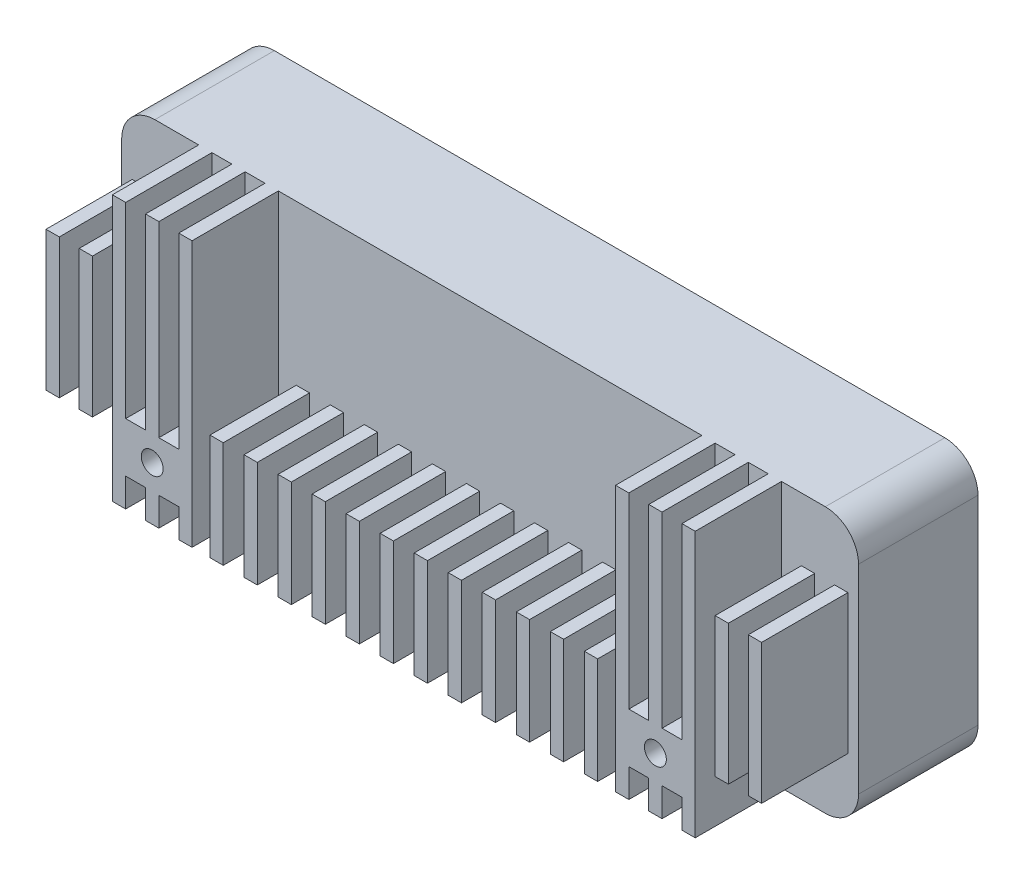
SolidWorks part; units mm, degrees
ref_plane "Plano frontal" through (0, 0, 0) normal (0, 0, 1) x (1, 0, 0)
ref_plane "Plano superior" through (0, 0, 0) normal (0, 1, 0) x (1, 0, 0)
ref_plane "Plano direito" through (0, 0, 0) normal (1, 0, 0) x (0, 0, -1)
sketch "Esboço1" plane through (0, 0, 0) normal (0, 0, 1) x (1, 0, 0)
  line L1 (55.5, -20) -> (-55.5, -20)
  line L2 (55.5, -20) -> (55.5, 20)
  line L3 (55.5, 20) -> (-55.5, 20)
  line L4 (-55.5, -20) -> (-55.5, 20)
  line L5 (55.5, -20) -> (-55.5, 20) construction
  line L6 (55.5, 20) -> (-55.5, -20) construction
  point P0 (0, 0)
  dimension "D1" = 40
  dimension "D2" = 111
extrude "Ressalto-extrusão1" add sketch "Esboço1" along normal blind 18
sketch "Esboço2" plane through (0, 0, 18) normal (0, 0, 1) x (1, 0, 0)
  line L0 (-55.5, -20) -> (55.5, -20) construction
  line L1 (-29.2, -4) -> (-27.2, -4)
  line L2 (-29.2, -4) -> (-29.2, -20)
  line L3 (-29.2, -20) -> (-27.2, -20)
  line L4 (-27.2, -4) -> (-27.2, -20)
  line L5 (-55.5, 20) -> (-55.5, -20) construction
  line L6 (-24.0727, -4) -> (-24.0727, -20)
  line L7 (-24.0727, -4) -> (-22.0727, -4)
  line L8 (-22.0727, -4) -> (-22.0727, -20)
  line L9 (-24.0727, -20) -> (-22.0727, -20)
  line L10 (-18.9455, -4) -> (-18.9455, -20)
  line L11 (-18.9455, -4) -> (-16.9455, -4)
  line L12 (-16.9455, -4) -> (-16.9455, -20)
  line L13 (-18.9455, -20) -> (-16.9455, -20)
  line L14 (-13.8182, -4) -> (-13.8182, -20)
  line L15 (-13.8182, -4) -> (-11.8182, -4)
  line L16 (-11.8182, -4) -> (-11.8182, -20)
  line L17 (-13.8182, -20) -> (-11.8182, -20)
  line L18 (-8.6909, -4) -> (-8.6909, -20)
  line L19 (-8.6909, -4) -> (-6.6909, -4)
  line L20 (-6.6909, -4) -> (-6.6909, -20)
  line L21 (-8.6909, -20) -> (-6.6909, -20)
  line L22 (-3.5636, -4) -> (-3.5636, -20)
  line L23 (-3.5636, -4) -> (-1.5636, -4)
  line L24 (-1.5636, -4) -> (-1.5636, -20)
  line L25 (-3.5636, -20) -> (-1.5636, -20)
  line L26 (1.5636, -4) -> (1.5636, -20)
  line L27 (1.5636, -4) -> (3.5636, -4)
  line L28 (3.5636, -4) -> (3.5636, -20)
  line L29 (1.5636, -20) -> (3.5636, -20)
  line L30 (6.6909, -4) -> (6.6909, -20)
  line L31 (6.6909, -4) -> (8.6909, -4)
  line L32 (8.6909, -4) -> (8.6909, -20)
  line L33 (6.6909, -20) -> (8.6909, -20)
  line L34 (11.8182, -4) -> (11.8182, -20)
  line L35 (11.8182, -4) -> (13.8182, -4)
  line L36 (13.8182, -4) -> (13.8182, -20)
  line L37 (11.8182, -20) -> (13.8182, -20)
  line L38 (16.9455, -4) -> (16.9455, -20)
  line L39 (16.9455, -4) -> (18.9455, -4)
  line L40 (18.9455, -4) -> (18.9455, -20)
  line L41 (16.9455, -20) -> (18.9455, -20)
  line L42 (22.0727, -4) -> (22.0727, -20)
  line L43 (22.0727, -4) -> (24.0727, -4)
  line L44 (24.0727, -4) -> (24.0727, -20)
  line L45 (22.0727, -20) -> (24.0727, -20)
  line L46 (27.2, -4) -> (27.2, -20)
  line L47 (27.2, -4) -> (29.2, -4)
  line L48 (29.2, -4) -> (29.2, -20)
  line L49 (27.2, -20) -> (29.2, -20)
  line L50 (55.5, -20) -> (55.5, 20) construction
  line L51 (-48.9, 10.5) -> (-48.9, -10.5)
  line L52 (-53.9, 10.5) -> (-51.9, 10.5)
  line L53 (-53.9, 10.5) -> (-53.9, -10.5)
  line L54 (-53.9, -10.5) -> (-51.9, -10.5)
  line L55 (-51.9, 10.5) -> (-51.9, -10.5)
  line L56 (-48.9, 10.5) -> (-46.9, 10.5)
  line L57 (-46.9, 10.5) -> (-46.9, -10.5)
  line L58 (-48.9, -10.5) -> (-46.9, -10.5)
  line L59 (-53.9, 10.5) -> (-48.9, 10.5) construction
  line L60 (55.5, 20) -> (-55.5, 20) construction
  line L61 (-43.9, 20) -> (-41.9, 20)
  line L62 (-43.9, 20) -> (-43.9, -20)
  line L63 (-43.9, -20) -> (-41.9, -20)
  line L64 (-41.9, 20) -> (-41.9, -20)
  line L65 (-38.9, 20) -> (-38.9, -20)
  line L66 (-38.9, 20) -> (-36.9, 20)
  line L67 (-36.9, 20) -> (-36.9, -20)
  line L68 (-38.9, -20) -> (-36.9, -20)
  line L69 (-33.9, 20) -> (-33.9, -20)
  line L70 (-33.9, 20) -> (-31.9, 20)
  line L71 (-31.9, 20) -> (-31.9, -20)
  line L72 (-33.9, -20) -> (-31.9, -20)
  line L73 (-43.9, 20) -> (-38.9, 20) construction
  line L74 (0, -9.9) -> (0, 9.9) construction
  line L75 (43.9, 20) -> (38.9, 20) construction
  line L76 (53.9, 10.5) -> (48.9, 10.5) construction
  line L77 (33.9, -20) -> (31.9, -20)
  line L78 (31.9, 20) -> (31.9, -20)
  line L79 (33.9, 20) -> (31.9, 20)
  line L80 (33.9, 20) -> (33.9, -20)
  line L81 (38.9, -20) -> (36.9, -20)
  line L82 (36.9, 20) -> (36.9, -20)
  line L83 (38.9, 20) -> (36.9, 20)
  line L84 (38.9, 20) -> (38.9, -20)
  line L85 (41.9, 20) -> (41.9, -20)
  line L86 (43.9, -20) -> (41.9, -20)
  line L87 (43.9, 20) -> (43.9, -20)
  line L88 (43.9, 20) -> (41.9, 20)
  line L89 (48.9, -10.5) -> (46.9, -10.5)
  line L90 (46.9, 10.5) -> (46.9, -10.5)
  line L91 (48.9, 10.5) -> (46.9, 10.5)
  line L92 (51.9, 10.5) -> (51.9, -10.5)
  line L93 (53.9, -10.5) -> (51.9, -10.5)
  line L94 (53.9, 10.5) -> (53.9, -10.5)
  line L95 (53.9, 10.5) -> (51.9, 10.5)
  line L96 (48.9, 10.5) -> (48.9, -10.5)
  point P8 (-55.5, 0)
  point P59 (-53.9, 0)
  dimension "D1" = 2
  dimension "D2" = 16
  dimension "D3" = 26.3
  dimension "D5" = 26.3
  dimension "D6" = 21
  dimension "D7" = 2
  dimension "D8" = 1.6
  dimension "D10" = 5
  dimension "D11" = 2
  dimension "D12" = 3
  dimension "D14" = 5
  dimension "D4" = 12
  dimension "D9" = 2
  dimension "D13" = 3
extrude "Ressalto-extrusão2" add sketch "Esboço2" along normal blind 13
sketch "Esboço3" plane through (0, 0, 31) normal (0, 0, 1) x (1, 0, 0)
  line L0 (-43.9, 20) -> (-43.9, -20) construction
  line L1 (-43.9, -15.7) -> (-31.9, -15.7)
  line L2 (-43.9, -15.7) -> (-43.9, -8.2)
  line L3 (-43.9, -8.2) -> (-31.9, -8.2)
  line L4 (-31.9, -15.7) -> (-31.9, -8.2)
  line L5 (-31.9, -20) -> (-31.9, 20) construction
  line L6 (-41.9, -20) -> (-38.9, -20) construction
  line L7 (0, -17.05) -> (0, 17.05) construction
  line L8 (31.9, -15.7) -> (31.9, -8.2)
  line L9 (43.9, -8.2) -> (31.9, -8.2)
  line L10 (43.9, -15.7) -> (43.9, -8.2)
  line L11 (43.9, -15.7) -> (31.9, -15.7)
  dimension "D1" = 4.3
  dimension "D2" = 7.5
extrude "Ressalto-extrusão3" add sketch "Esboço3" against normal up to next
sketch "Esboço4" plane through (0, 0, 31) normal (0, 0, 1) x (1, 0, 0)
  line L0 (-38.9, -20) -> (-36.9, -20) construction
  line L1 (-41.9, -8.2) -> (-41.9, -15.7) construction
  line L2 (0, -17.05) -> (0, 17.05) construction
  circle A0 centre (-37.9, -11.95) radius 1.65
  circle A1 centre (37.9, -11.95) radius 1.65
  point P4 (-37.9, -20)
  point P9 (-41.9, -11.95)
  dimension "D1" = 3.3
extrude "Corte-extrusão1" cut sketch "Esboço4" against normal blind 6
fillet "Filete1" radius 5 4 edges at (-55.5, -20, 9) (-55.5, 20, 9) (55.5, -20, 9) (55.5, 20, 9)
